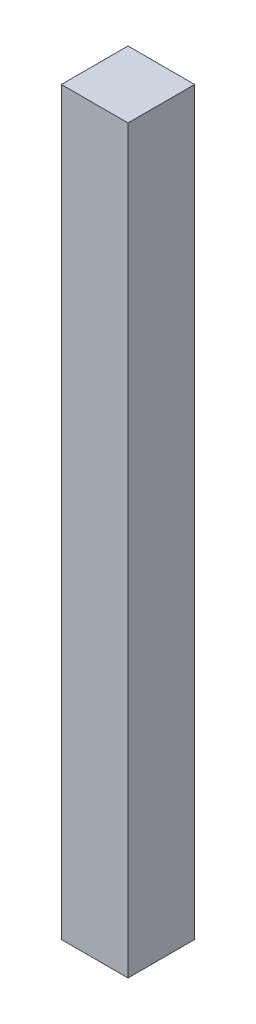
SolidWorks part; units mm, degrees
ref_plane "Front Plane" through (0, 0, 0) normal (0, 0, 1) x (1, 0, 0)
ref_plane "Top Plane" through (0, 0, 0) normal (0, 1, 0) x (1, 0, 0)
ref_plane "Right Plane" through (0, 0, 0) normal (1, 0, 0) x (0, 0, -1)
other "Configuration Table"
sketch "Sketch1" plane through (0, 0, 0) normal (0, 0, 1) x (1, 0, 0)
  line L1 (84, 436) -> (102, 436)
  line L2 (84, 436) -> (84, 636)
  line L3 (84, 636) -> (102, 636)
  line L4 (102, 436) -> (102, 636)
extrude "STORE_klape_kaset_kati_gazli_amortisor_1_1" add sketch "Sketch1" against normal blind 18 from offset 12 separate body
